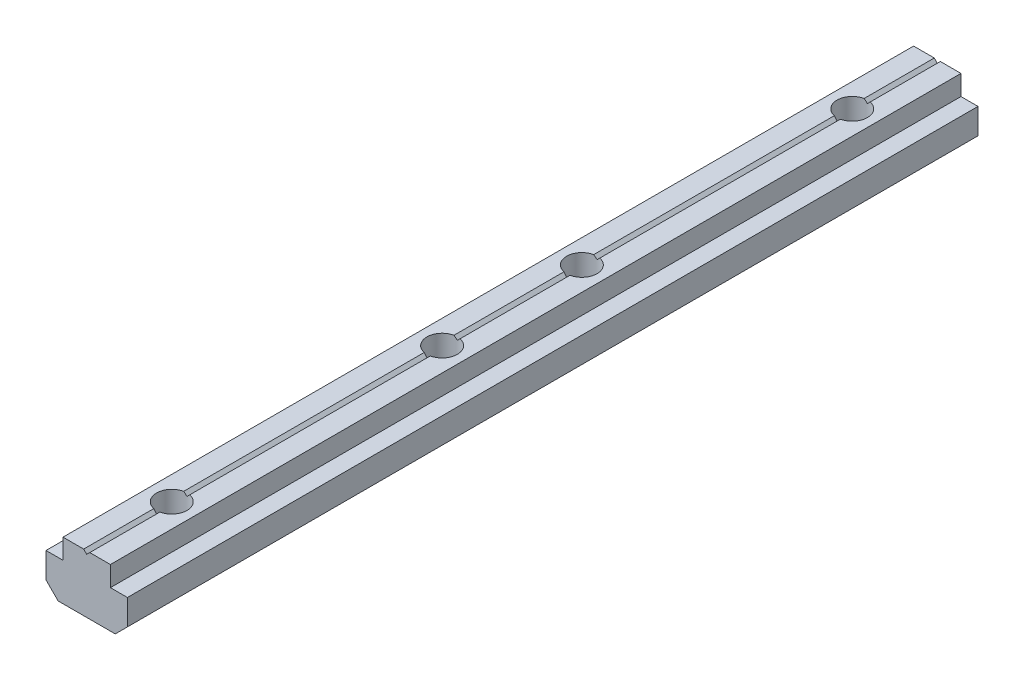
SolidWorks part; units mm, degrees
ref_plane "前视基准面" through (0, 0, 0) normal (0, 0, 1) x (1, 0, 0)
ref_plane "上视基准面" through (0, 0, 0) normal (0, 1, 0) x (1, 0, 0)
ref_plane "右视基准面" through (0, 0, 0) normal (1, 0, 0) x (0, 0, -1)
sketch "草图1" plane through (0, 0, 0) normal (0, 0, 1) x (1, 0, 0)
  line B0 (-2, -6.2) -> (-11.4, -6.2)
  line B1 (-10.6, 3.3) -> (-7.2, 3.3)
  line B2 (-6.2, 3.3) -> (-2.8, 3.3)
  line B3 (-13.4, 0) -> (-10.6, 0)
  line B4 (-2.8, 0) -> (0, 0)
  line B5 (0, 0) -> (0, -4.2)
  line B6 (-13.4, 0) -> (-13.4, -4.2)
  line B7 (-2.8, 3.3) -> (-2.8, 0)
  line B8 (-10.6, 3.3) -> (-10.6, 0)
  line B9 (-11.4, -6.2) -> (-13.4, -4.2)
  line B10 (-2, -6.2) -> (0, -4.2)
  line B11 (-6.7, 2.8) -> (-7.2, 3.3)
  line B12 (-6.7, 2.8) -> (-6.2, 3.3)
sketch_block_instance "A$C3ECF06B9-1"
sketch_block "A$C3ECF06B9"
extrude "凸台-拉伸1" add sketch "草图1" along normal blind 140
sketch "草图5" plane through (0, -6.2, 0) normal (0, -1, 0) x (1, 0, 0)
  line L0 (-11.4, 70) -> (-2, 70) construction
  line L1 (-11.4, 140) -> (-11.4, 0) construction
  line L2 (-2, 140) -> (-2, 0) construction
  point P6 (-6.7, 14)
  point P7 (-6.7, 81.5)
  point P8 (-6.7, 58.5)
  point P9 (-6.7, 126)
  dimension "D1" = 56
  dimension "D2" = 2
hole_wizard "M6 螺纹孔1" positions "3D草图2" profile "草图6" tap size "M6" standard "Iso"
sketch3d "3D草图2"
  point P0 (-6.7, -6.2, 14)
  point P3 (-6.7, -6.2, 58.5)
  point P6 (-6.7, -6.2, 81.5)
  point P9 (-6.7, -6.2, 126)
sketch "草图6" plane through (-6.7, -6.2, 14) normal (1, 0, 0) x (0, 0, -1)
  line L0 (0, 0) -> (0, 29.5022)
  line L1 (0, 29.5022) -> (2.5, 28)
  line L2 (2.5, 28) -> (2.5, 0)
  line L5 (2.5, 0) -> (0, 0)
  line L10 (0, 29.5022) -> (-2.5, 28) construction
  line L11 (0, -6.35) -> (0, 107.95) construction
  dimension "螺纹孔钻头直径" = 5
  dimension "螺纹孔钻头深度" = 28
  dimension "导头角度" = 118
cosmetic thread "孔螺蚊线1"
cosmetic thread "孔螺蚊线2"
cosmetic thread "孔螺蚊线3"
cosmetic thread "孔螺蚊线4"
